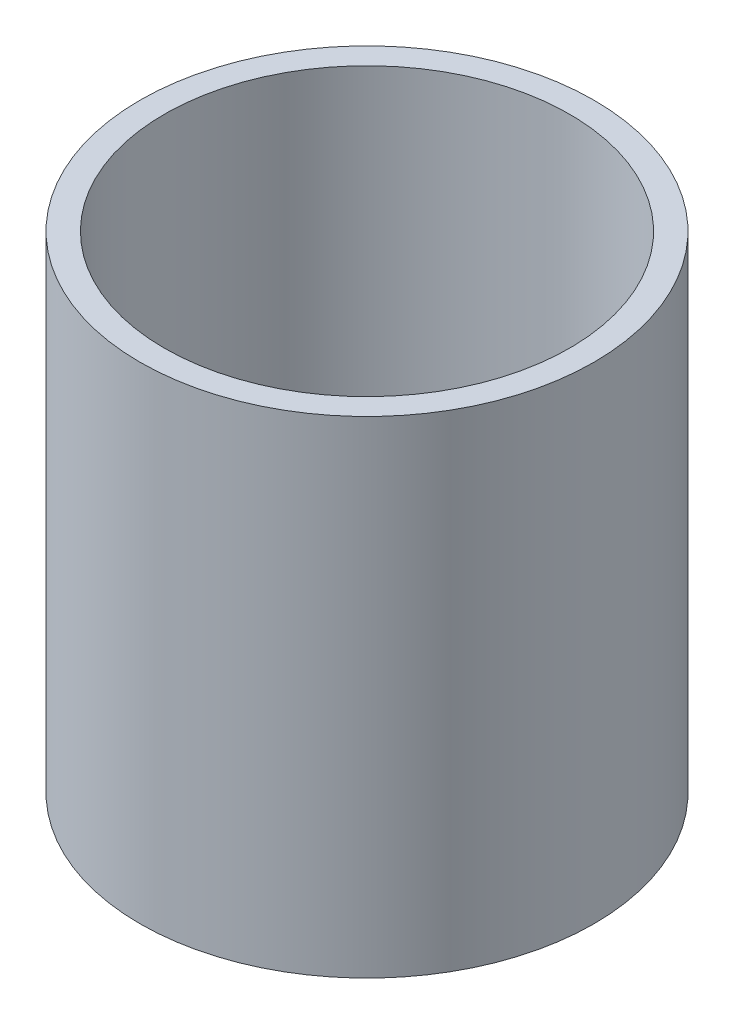
SolidWorks part; units mm, degrees
ref_plane "Front Plane" through (0, 0, 0) normal (0, 0, 1) x (1, 0, 0)
ref_plane "Top Plane" through (0, 0, 0) normal (0, 1, 0) x (1, 0, 0)
ref_plane "Right Plane" through (0, 0, 0) normal (1, 0, 0) x (0, 0, -1)
sketch "Sketch1" plane through (0, 0, 0) normal (0, 1, 0) x (1, 0, 0)
  circle A0 centre (0, 0) radius 25
  circle A1 centre (0, 0) radius 28
  dimension "D1" = 50
  dimension "D2" = 3
extrude "Boss-Extrude1" add sketch "Sketch1" along normal blind 60
